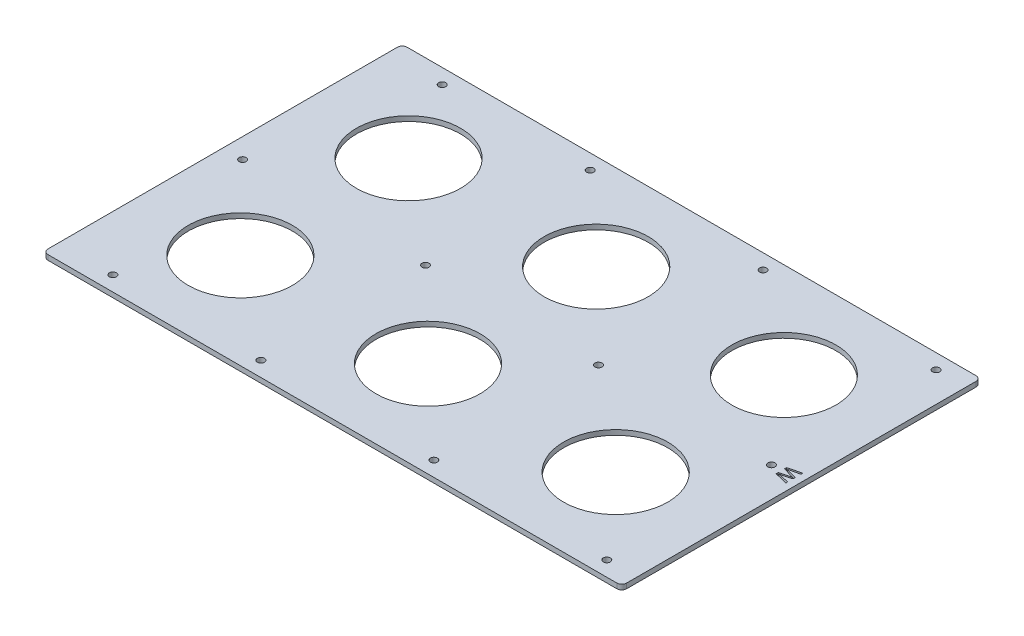
SolidWorks part; units mm, degrees
material "ABS"
ref_plane "Front" through (0, 0, 0) normal (0, 0, 1) x (1, 0, 0)
ref_plane "Top" through (0, 0, 0) normal (0, 1, 0) x (1, 0, 0)
ref_plane "Right" through (0, 0, 0) normal (1, 0, 0) x (0, 0, -1)
sketch "Sketch1" plane through (0, 0, 0) normal (0, 1, 0) x (1, 0, 0)
  line L1 (-180.975, 114.3) -> (180.975, 114.3)
  line L2 (-184.15, 111.125) -> (-184.15, -111.125)
  line L3 (-180.975, -114.3) -> (180.975, -114.3)
  line L4 (184.15, 111.125) -> (184.15, -111.125)
  line L5 (-184.15, 114.3) -> (184.15, -114.3) construction
  line L6 (-184.15, -114.3) -> (184.15, 114.3) construction
  circle A0 centre (119.5086, -53.5178) radius 33.147
  arc A1 (-184.15, -111.125) -> (-180.975, -114.3) centre (-180.975, -111.125) ccw
  arc A2 (180.975, -114.3) -> (184.15, -111.125) centre (180.975, -111.125) ccw
  arc A3 (184.15, 111.125) -> (180.975, 114.3) centre (180.975, 111.125) ccw
  arc A4 (-180.975, 114.3) -> (-184.15, 111.125) centre (-180.975, 111.125) ccw
  circle A5 centre (165.1, 0) radius 2.2479 construction
  circle A6 centre (165.1, 0) radius 2.2479
  circle A7 centre (-171.45, 0) radius 2.2479 construction
  circle A8 centre (-171.45, 0) radius 2.2479
  circle A21 centre (-55.0333, 0) radius 2.2479 construction
  circle A22 centre (55.0333, 0) radius 2.2479 construction
  circle A23 centre (-55.0333, 0) radius 2.2479
  circle A24 centre (55.0333, 0) radius 2.2479
  circle A25 centre (119.5086, 53.5178) radius 33.147
  circle A26 centre (0.0643, 53.5178) radius 33.147
  circle A27 centre (0.0643, -53.5178) radius 33.147
  circle A28 centre (-119.38, 53.5178) radius 33.147
  circle A29 centre (-119.38, -53.5178) radius 33.147
  arc A34 (-143.7521, 103.8733) -> (-143.7521, 3.1623) centre (-119.38, 53.5178) ccw construction
  arc A35 (-24.3078, 103.8733) -> (-24.3078, 3.1623) centre (0.0643, 53.5178) ccw construction
  arc A36 (95.1365, 103.8733) -> (95.1365, 3.1623) centre (119.5086, 53.5178) ccw construction
  arc A37 (-143.7521, -3.1623) -> (-143.7521, -103.8733) centre (-119.38, -53.5178) ccw construction
  arc A38 (-24.3078, -3.1623) -> (-24.3078, -103.8733) centre (0.0643, -53.5178) ccw construction
  arc A39 (95.1365, -3.1623) -> (95.1365, -103.8733) centre (119.5086, -53.5178) ccw construction
  circle A40 centre (-149.225, -104.775) radius 2.2479 construction
  circle A41 centre (-55.0333, -104.775) radius 2.2479 construction
  circle A42 centre (55.0333, -104.775) radius 2.2479 construction
  circle A43 centre (165.1, -104.775) radius 2.2479 construction
  circle A44 centre (-149.225, 104.775) radius 2.2479 construction
  circle A45 centre (-55.0333, 104.775) radius 2.2479 construction
  circle A46 centre (55.0333, 104.775) radius 2.2479 construction
  circle A47 centre (165.1, 104.775) radius 2.2479 construction
  circle A48 centre (-149.225, -104.775) radius 2.2479
  circle A49 centre (-55.0333, -104.775) radius 2.2479
  circle A50 centre (55.0333, -104.775) radius 2.2479
  circle A51 centre (165.1, -104.775) radius 2.2479
  circle A52 centre (-149.225, 104.775) radius 2.2479
  circle A53 centre (-55.0333, 104.775) radius 2.2479
  circle A54 centre (55.0333, 104.775) radius 2.2479
  circle A55 centre (165.1, 104.775) radius 2.2479
  point P0 (0, 0)
  dimension "D3" = 66.294
  dimension "D4" = 3.175
  dimension "D1" = 368.3
  dimension "D2" = 228.6
extrude "Boss-Extrude1" add sketch "Sketch1" along normal blind 3.175
sketch "Sketch2" plane through (0, 3.175, 0) normal (0, 1, 0) x (1, 0, 0)
  line L0 (171.45, 30) -> (171.45, -30) construction
  line L1 (0, 0) -> (184.15, 0) construction
  line L2 (184.15, -111.125) -> (184.15, 111.125) construction
  text T0 "W" font "Arial" height in points 32
  point P7 (171.45, 0)
  dimension "D1" = 12.7
  dimension "D2" = 60
extrude "Cut-Extrude1" cut sketch "Sketch2" against normal blind 1.524
sketch "Sketch3" [suppressed] plane through (0, 0, 0) normal (0, 1, 0) x (1, 0, 0)
  line L0 (577.85, -114.3) -> (577.85, 114.3)
  line L1 (-209.55, 127) -> (1009.65, 127)
  line L2 (-209.55, 127) -> (-209.55, -1092.2)
  line L3 (-209.55, -1092.2) -> (1009.65, -1092.2)
  line L4 (1009.65, 127) -> (1009.65, -1092.2)
  line L5 (184.15, -114.3) -> (-184.15, -114.3)
  line L6 (184.15, -114.3) -> (184.15, 114.3)
  line L7 (184.15, 114.3) -> (-184.15, 114.3)
  line L8 (-184.15, -114.3) -> (-184.15, 114.3)
  line L9 (577.85, -114.3) -> (209.55, -114.3)
  line L10 (209.55, -114.3) -> (209.55, 114.3)
  line L11 (577.85, 114.3) -> (209.55, 114.3)
  line L12 (971.55, -114.3) -> (971.55, 114.3)
  line L13 (971.55, -114.3) -> (603.25, -114.3)
  line L14 (603.25, -114.3) -> (603.25, 114.3)
  line L15 (971.55, 114.3) -> (603.25, 114.3)
  line L16 (577.85, -355.6) -> (577.85, -127)
  line L17 (577.85, -355.6) -> (209.55, -355.6)
  line L18 (209.55, -355.6) -> (209.55, -127)
  line L19 (577.85, -127) -> (209.55, -127)
  line L20 (971.55, -355.6) -> (971.55, -127)
  line L21 (971.55, -355.6) -> (603.25, -355.6)
  line L22 (603.25, -355.6) -> (603.25, -127)
  line L23 (971.55, -127) -> (603.25, -127)
  line L24 (184.15, -355.6) -> (184.15, -127)
  line L25 (184.15, -355.6) -> (-184.15, -355.6)
  line L26 (-184.15, -355.6) -> (-184.15, -127)
  line L27 (184.15, -127) -> (-184.15, -127)
  line L28 (184.15, -596.9) -> (184.15, -368.3)
  line L29 (184.15, -596.9) -> (-184.15, -596.9)
  line L30 (-184.15, -596.9) -> (-184.15, -368.3)
  line L31 (184.15, -368.3) -> (-184.15, -368.3)
  line L32 (577.85, -596.9) -> (577.85, -368.3)
  line L33 (577.85, -596.9) -> (209.55, -596.9)
  line L34 (209.55, -596.9) -> (209.55, -368.3)
  line L35 (577.85, -368.3) -> (209.55, -368.3)
  line L36 (971.55, -596.9) -> (971.55, -368.3)
  line L37 (971.55, -596.9) -> (603.25, -596.9)
  line L38 (603.25, -596.9) -> (603.25, -368.3)
  line L39 (971.55, -368.3) -> (603.25, -368.3)
  line L40 (184.15, -838.2) -> (184.15, -609.6)
  line L41 (184.15, -838.2) -> (-184.15, -838.2)
  line L42 (-184.15, -838.2) -> (-184.15, -609.6)
  line L43 (184.15, -609.6) -> (-184.15, -609.6)
  line L44 (577.85, -838.2) -> (577.85, -609.6)
  line L45 (577.85, -838.2) -> (209.55, -838.2)
  line L46 (209.55, -838.2) -> (209.55, -609.6)
  line L47 (577.85, -609.6) -> (209.55, -609.6)
  line L48 (971.55, -838.2) -> (971.55, -609.6)
  line L49 (971.55, -838.2) -> (603.25, -838.2)
  line L50 (603.25, -838.2) -> (603.25, -609.6)
  line L51 (971.55, -609.6) -> (603.25, -609.6)
  line L52 (184.15, -1079.5) -> (184.15, -850.9)
  line L53 (184.15, -1079.5) -> (-184.15, -1079.5)
  line L54 (-184.15, -1079.5) -> (-184.15, -850.9)
  line L55 (184.15, -850.9) -> (-184.15, -850.9)
  line L56 (577.85, -1079.5) -> (577.85, -850.9)
  line L57 (577.85, -1079.5) -> (209.55, -1079.5)
  line L58 (209.55, -1079.5) -> (209.55, -850.9)
  line L59 (577.85, -850.9) -> (209.55, -850.9)
  line L60 (971.55, -1079.5) -> (971.55, -850.9)
  line L61 (971.55, -1079.5) -> (603.25, -1079.5)
  line L62 (603.25, -1079.5) -> (603.25, -850.9)
  line L63 (971.55, -850.9) -> (603.25, -850.9)
  line L64 (180.975, 114.3) -> (-180.975, 114.3) construction
  line L65 (-180.975, -114.3) -> (180.975, -114.3) construction
  line L66 (-184.15, 111.125) -> (-184.15, -111.125) construction
  line L67 (184.15, -111.125) -> (184.15, 111.125) construction
  line L68 (209.55, 114.3) -> (184.15, 114.3) construction
  line L69 (-184.15, -114.3) -> (-184.15, -127) construction
  line L70 (196.85, 127) -> (196.85, -120.65) construction
  line L71 (196.85, -120.65) -> (-209.55, -120.65) construction
  line L72 (-184.15, -355.6) -> (-184.15, -368.3) construction
  line L73 (-184.15, -361.95) -> (-209.55, -361.95) construction
  line L74 (603.25, 114.3) -> (577.85, 114.3) construction
  line L75 (590.55, 114.3) -> (590.55, 127) construction
  line L76 (-184.15, -596.9) -> (-184.15, -609.6) construction
  line L77 (-184.15, -838.2) -> (-184.15, -850.9) construction
  line L78 (-184.15, -844.55) -> (-209.55, -844.55) construction
  line L79 (-184.15, -603.25) -> (-209.55, -603.25) construction
  point P75 (-184.15, -120.65)
  point P77 (196.85, 114.3)
  dimension "D1" = 1219.2
  dimension "D2" = 1219.2
  dimension "D5" = 12.7
  dimension "D6" = 12.7
  dimension "D7" = 25.4
  dimension "D8" = 25.4
  dimension "D9" = 247.65
  dimension "D10" = 406.4
  dimension "D11" = 247.65
  dimension "D12" = 241.3
  dimension "D13" = 393.7
  dimension "D14" = 419.1
  dimension "D15" = 241.3
  dimension "D16" = 247.65
  dimension "D17" = 241.3
  dimension "D3" = 3
  dimension "D4" = 5
